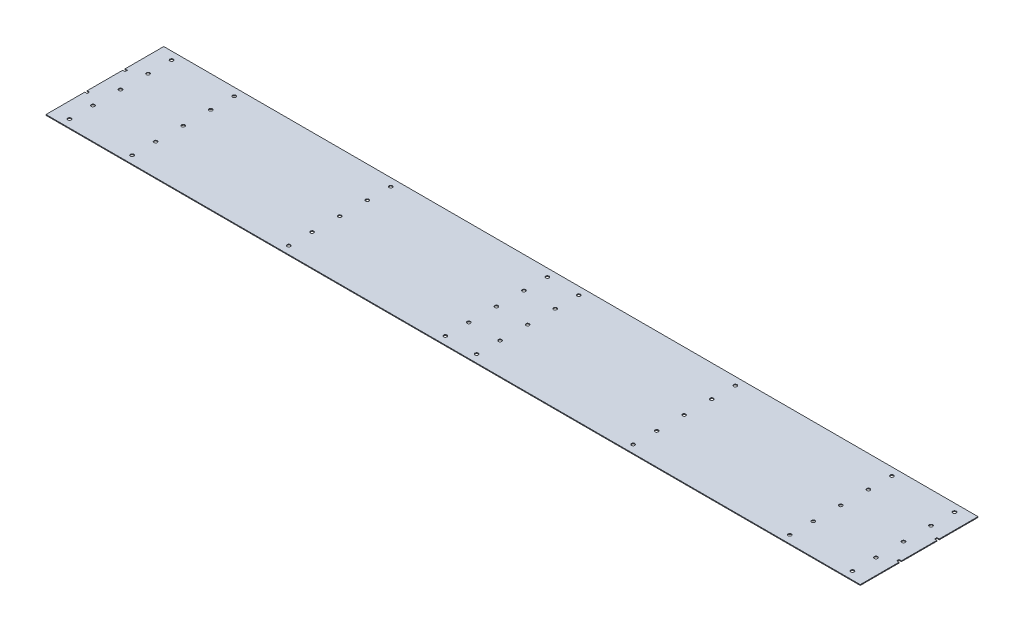
SolidWorks part; units mm, degrees
ref_plane "Front Plane" through (0, 0, 0) normal (0, 0, 1) x (1, 0, 0)
ref_plane "Top Plane" through (0, 0, 0) normal (0, 1, 0) x (1, 0, 0)
ref_plane "Right Plane" through (0, 0, 0) normal (1, 0, 0) x (0, 0, -1)
sketch "Sketch1" plane through (0, 0, 0) normal (0, 1, 0) x (1, 0, 0)
  line L0 (-500, -25.7) -> (-500, -75.2)
  line L1 (-500, -75.2) -> (540, -75.2)
  line L2 (540, -75.2) -> (540, -25.7)
  line L3 (540, -25.7) -> (-500, -25.7) construction
  line L4 (0, 0) -> (-497, 0) construction
  line L5 (-500, -25.7) -> (-497, -25.7)
  line L7 (-497, 25.7) -> (-500, 25.7)
  line L8 (-500, 25.7) -> (-500, 75.2)
  line L9 (-500, 75.2) -> (540, 75.2)
  line L10 (540, 75.2) -> (540, 25.7)
  line L11 (540, 25.7) -> (537, 25.7)
  line L13 (537, -25.7) -> (540, -25.7)
  line L14 (0, 35.2) -> (520, 35.2) construction
  line L15 (-497, 25.7) -> (-497, 22.7)
  line L16 (-497, 25.7) -> (537, 25.7) construction
  line L17 (537, 25.7) -> (537, -25.7) construction
  line L18 (-497, 25.7) -> (-497, -25.7) construction
  line L19 (-497, 22.7) -> (-500, 22.7)
  line L20 (-500, 22.7) -> (-500, -22.7)
  line L21 (-500, -22.7) -> (-497, -22.7)
  line L22 (-497, -22.7) -> (-497, -25.7)
  line L23 (537, 25.7) -> (537, 22.7)
  line L24 (537, 22.7) -> (540, 22.7)
  line L25 (540, 22.7) -> (540, -22.7)
  line L26 (540, -22.7) -> (537, -22.7)
  line L27 (537, -22.7) -> (537, -25.7)
  line L28 (540, 0) -> (537, 0) construction
  line L29 (520, 35.2) -> (520, -35.2) construction
  line L30 (-497, 0) -> (-500, 0) construction
  line L31 (0, 35.2) -> (0, -35.2) construction
  line L32 (520, -35.2) -> (0, -35.2) construction
  line L33 (0, 35.2) -> (0, 65.2) construction
  line L34 (0, 65.2) -> (520, 65.2) construction
  line L35 (520, 65.2) -> (520, 35.2) construction
  line L36 (520, -35.2) -> (520, -65.2) construction
  line L37 (520, -65.2) -> (0, -65.2) construction
  line L38 (0, -65.2) -> (0, -35.2) construction
  line L39 (0, 0) -> (520, 0) construction
  line L40 (-200, 65.2) -> (-200, 35.2) construction
  line L41 (-200, 35.2) -> (-200, 0) construction
  line L42 (-200, 0) -> (-200, -35.2) construction
  line L43 (-200, -35.2) -> (-200, -65.2) construction
  line L44 (40, 65.2) -> (40, -65.2) construction
  line L45 (-400, 65.2) -> (-480, 65.2) construction
  line L46 (-480, 65.2) -> (-480, -65.2) construction
  line L47 (-480, -65.2) -> (-400, -65.2) construction
  line L48 (-400, -65.2) -> (-400, 65.2) construction
  line L49 (-400, 65.2) -> (0, 65.2) construction
  line L50 (440, 65.2) -> (440, -65.2) construction
  line L51 (-400, 35.2) -> (0, 35.2) construction
  line L52 (440, -65.2) -> (520, -65.2) construction
  line L53 (-400, -35.2) -> (0, -35.2) construction
  line L55 (-480, -65.2) -> (0, -65.2) construction
  line L56 (440, -35.2) -> (520, -35.2) construction
  line L58 (440, 0) -> (520, 0) construction
  line L60 (440, 35.2) -> (520, 35.2) construction
  line L62 (440, 65.2) -> (520, 65.2) construction
  circle A0 centre (0, -35.2) radius 2.15
  circle A30 centre (0, 35.2) radius 2.15
  circle A31 centre (0, -65.2) radius 2.15
  circle A32 centre (0, 65.2) radius 2.15
  circle A33 centre (-200, -65.2) radius 2.15
  circle A34 centre (-200, -35.2) radius 2.15
  circle A35 centre (-200, 35.2) radius 2.15
  circle A36 centre (-200, 65.2) radius 2.15
  circle A53 centre (0, 0) radius 2.15
  circle A55 centre (-200, 0) radius 2.15
  circle A56 centre (-400, 0) radius 2.15
  circle A57 centre (-400, -65.2) radius 2.15
  circle A58 centre (-400, -35.2) radius 2.15
  circle A59 centre (-400, 35.2) radius 2.15
  circle A60 centre (-400, 65.2) radius 2.15
  circle A61 centre (40, -65.2) radius 2.15
  circle A62 centre (40, -35.2) radius 2.15
  circle A63 centre (40, 0) radius 2.15
  circle A64 centre (40, 35.2) radius 2.15
  circle A65 centre (40, 65.2) radius 2.15
  circle A66 centre (520, 65.2) radius 2.15
  circle A67 centre (520, 35.2) radius 2.15
  circle A68 centre (520, 0) radius 2.15
  circle A69 centre (520, -35.2) radius 2.15
  circle A70 centre (520, -65.2) radius 2.15
  circle A71 centre (240, -65.2) radius 2.15
  circle A72 centre (240, -35.2) radius 2.15
  circle A73 centre (240, 0) radius 2.15
  circle A74 centre (240, 35.2) radius 2.15
  circle A75 centre (240, 65.2) radius 2.15
  circle A76 centre (440, -65.2) radius 2.15
  circle A77 centre (440, -35.2) radius 2.15
  circle A78 centre (440, 0) radius 2.15
  circle A79 centre (440, 35.2) radius 2.15
  circle A80 centre (440, 65.2) radius 2.15
  circle A81 centre (-480, 65.2) radius 2.15
  circle A82 centre (-480, 35.2) radius 2.15
  circle A83 centre (-480, 0) radius 2.15
  circle A84 centre (-480, -65.2) radius 2.15
  circle A85 centre (-480, -35.2) radius 2.15
  dimension "D12" = 4.3
  dimension "D13" = 12.5
  dimension "D11" = 200
  dimension "D2" = 45.4
  dimension "D3" = 3
  dimension "D6" = 10
  dimension "D7" = 30
  dimension "D16" = 12.5
  dimension "D8" = 3
  dimension "D4" = 40
  dimension "D17" = 200
  dimension "D5" = 80
  dimension "D15" = 20
  dimension "D18" = 80
  dimension "D19" = 20
  dimension "D20" = 1040
  dimension "D9" = 3
  dimension "D14" = 3
  dimension "D10" = 3
extrude "Boss-Extrude1" add sketch "Sketch1" along normal blind 1
equation "\"skin_sheetmetal_thickness\"= 0.80"
equation "\"base_width_skin_spacer\" = \"base_width_skin_target_width\" - 4 * \"skin_sheetmetal_thickness\" - 2 * \"base_width_skin_target_bend_radius\""
equation "\"base_width_skin_inner\" = \"base_width_skin_spacer\" + 2 * \"skin_sheetmetal_thickness\""
equation "\"base_width_skin_outer\" = \"base_width_skin_inner\" + 2 * \"skin_sheetmetal_thickness\""
equation "\"bend_cut_width\"= 3"
equation "\"bend_cut_length\"= 3"
equation "\"bend_offset_inner\"= 12.5"
equation "\"bend_offset_outer\" = \"bend_offset_inner\" + \"skin_sheetmetal_thickness\""
equation "\"border_offset_ends\"= 20"
equation "\"border_offset_sides\"= 10"
equation "\"border_offset_flange_horiz\"= 10"
equation "\"rivet_size\"= 4.3"
equation "\"rivet_offset_ends\"= \"rivet_spacing_horiz\"/2 - \"border_offset_ends\""
equation "\"rivet_spacing_horiz\"= 200"
equation "\"rivet_spacing_vert\"= 30"
equation "\"rivet_spacing_offset_right\"= 40"
equation "\"base_length\"= 200"
equation "\"base_width_skin_spacer_length\" = 315"
equation "\"bend_offset_spacer_tab\"= 21.0"
equation "\"D2@Sketch1\"=\"base_width_skin_inner\""
equation "\"D3@Sketch1\"=\"bend_cut_length\""
equation "\"D8@Sketch1\"=\"bend_cut_width\""
equation "\"D16@Sketch1\"=\"bend_offset_inner\""
equation "\"D7@Sketch1\"=\"rivet_spacing_vert\""
equation "\"D12@Sketch1\"=\"rivet_size\""
equation "\"D6@Sketch1\"=\"border_offset_flange_horiz\""
equation "\"D11@Sketch1\"=\"rivet_spacing_horiz\""
equation "\"D4@Sketch1\"=\"rivet_spacing_offset_right\""
equation "\"D17@Sketch1\"=\"rivet_spacing_horiz\""
equation "\"D5@Sketch1\"=\"rivet_offset_ends\""
equation "\"D15@Sketch1\"=\"border_offset_ends\""
equation "\"D18@Sketch1\"=\"rivet_offset_ends\""
equation "\"D19@Sketch1\"=\"border_offset_ends\""
equation "\"base_width_skin_target_width\" = 50"
equation "\"base_width_skin_target_bend_radius\" = 1.5"
